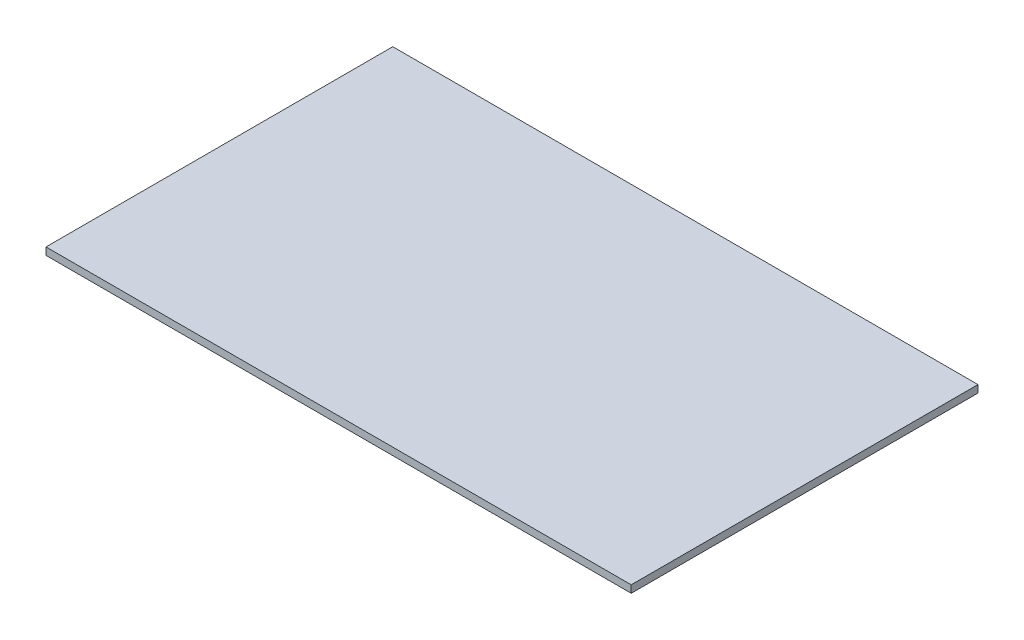
SolidWorks part; units mm, degrees
material "2.0060 (Cu-ETP)"
ref_plane "Alzado" through (0, 0, 0) normal (0, 0, 1) x (1, 0, 0)
ref_plane "Planta" through (0, 0, 0) normal (0, 1, 0) x (1, 0, 0)
ref_plane "Vista lateral" through (0, 0, 0) normal (1, 0, 0) x (0, 0, -1)
sketch "Croquis1" plane through (0, 0, 0) normal (0, 1, 0) x (1, 0, 0)
  line L1 (67.5, -40) -> (-67.5, -40)
  line L2 (67.5, -40) -> (67.5, 40)
  line L3 (67.5, 40) -> (-67.5, 40)
  line L4 (-67.5, -40) -> (-67.5, 40)
  line L5 (67.5, -40) -> (-67.5, 40) construction
  line L6 (67.5, 40) -> (-67.5, -40) construction
  point P0 (0, 0)
  dimension "D1" = 135
  dimension "D2" = 80
extrude "Saliente-Extruir1" add sketch "Croquis1" along normal blind 1.7
